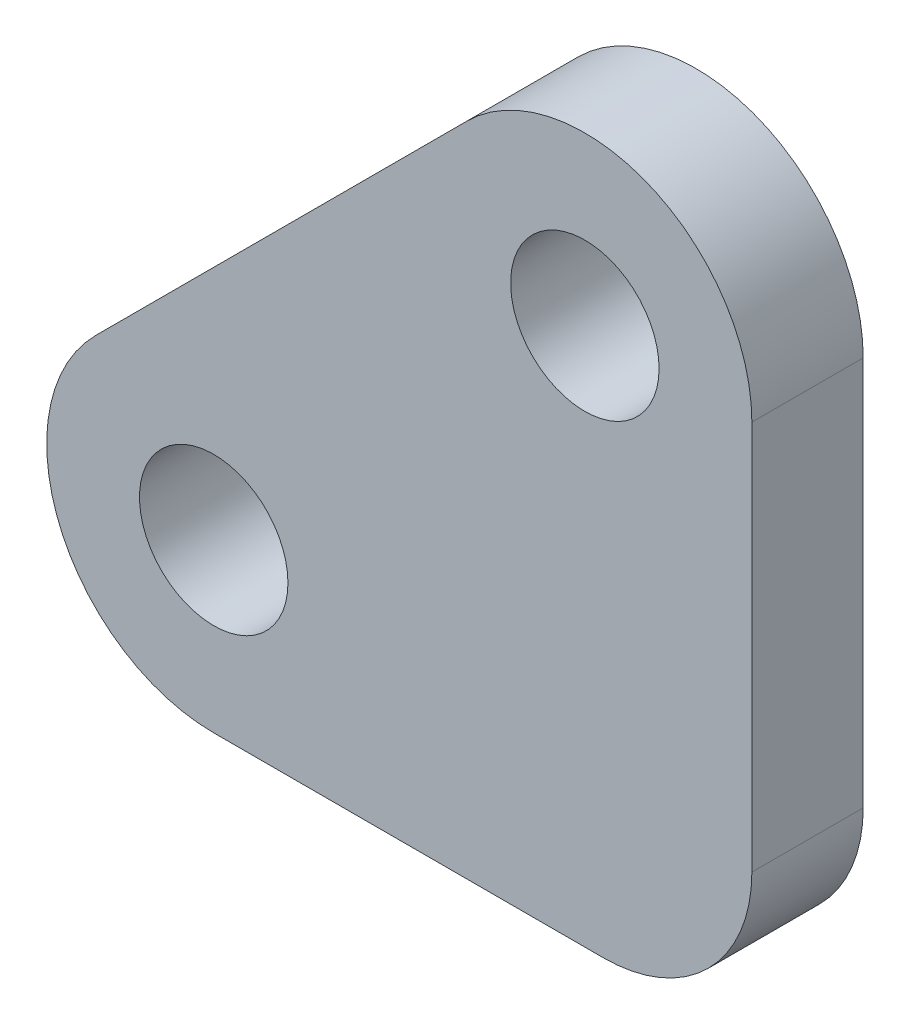
SolidWorks part; units mm, degrees
ref_plane "Plan de face" through (0, 0, 0) normal (0, 0, 1) x (1, 0, 0)
ref_plane "Plan de dessus" through (0, 0, 0) normal (0, 1, 0) x (1, 0, 0)
ref_plane "Plan de droite" through (0, 0, 0) normal (1, 0, 0) x (0, 0, -1)
sketch "Esquisse1" plane through (0, 0, 0) normal (0, 0, 1) x (1, 0, 0)
  line L0 (0, 0) -> (0, -20.7539) construction
  line L1 (0, 0) -> (18.2585, 0) construction
  line L2 (-5, -9.5) -> (9.5, -9.5)
  line L3 (1.818, 8.182) -> (-8.182, -1.818)
  line L4 (9.5, 5) -> (9.5, -9.5)
  circle A0 centre (5, 5) radius 2
  circle A1 centre (-5, -5) radius 2
  arc A2 (-8.182, -1.818) -> (-5, -9.5) centre (-5, -5) ccw
  arc A3 (9.5, 5) -> (1.818, 8.182) centre (5, 5) ccw
  dimension "D2" = 4
  dimension "D3" = 4
  dimension "D7" = 4.5
  dimension "D8" = 4.5
  dimension "D1" = 5
  dimension "D4" = 5
  dimension "D5" = 5
  dimension "D6" = 5
extrude "Boss.-Extru.1" add sketch "Esquisse1" along normal blind 3
fillet "Congé1" radius 4 1 edges at (9.5, -9.5, 1.5)
